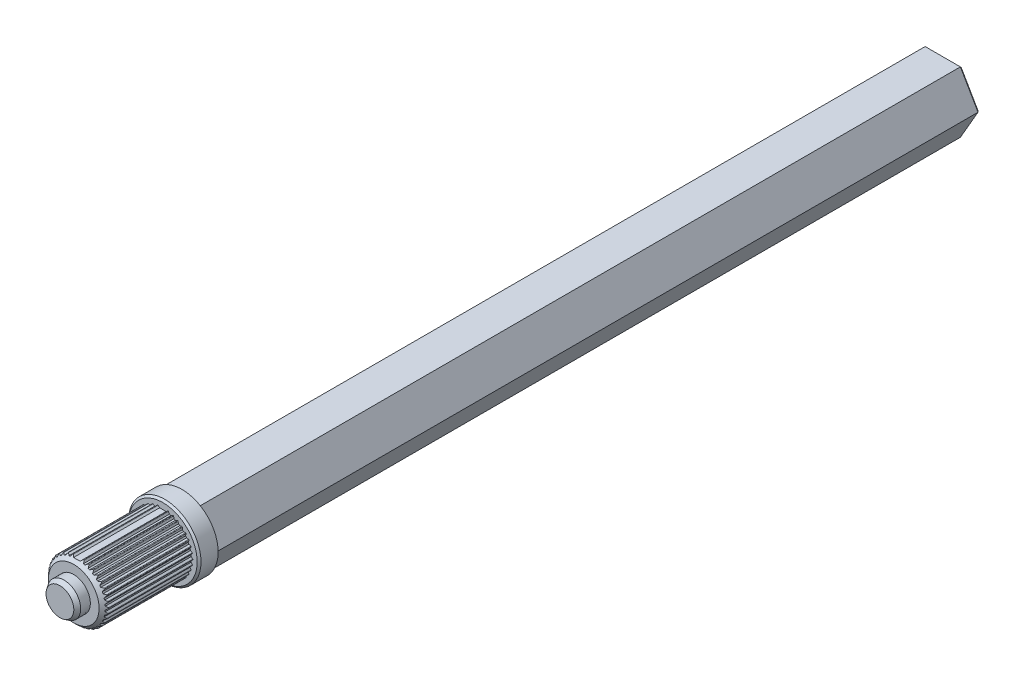
SolidWorks part; units mm, degrees
material "201 Tavlı Paslanmaz Çelik (SS)"
ref_plane "Ön Düzlem" through (0, 0, 0) normal (0, 0, 1) x (1, 0, 0)
ref_plane "Üst Düzlem" through (0, 0, 0) normal (0, 1, 0) x (1, 0, 0)
ref_plane "Sağ Düzlem" through (0, 0, 0) normal (1, 0, 0) x (0, 0, -1)
sketch "Çizim1" plane through (0, 0, 0) normal (0, 0, 1) x (1, 0, 0)
  line L1 (9.2376, 0) -> (4.6188, 8)
  line L2 (4.6188, 8) -> (-4.6188, 8)
  line L3 (-4.6188, 8) -> (-9.2376, 0)
  line L4 (-9.2376, 0) -> (-4.6188, -8)
  line L5 (-4.6188, -8) -> (4.6188, -8)
  line L6 (4.6188, -8) -> (9.2376, 0)
  circle A0 centre (0, 0) radius 8 construction
  dimension "D1" = 16
extrude "Yükseklik-Ekstrüzyon1" add sketch "Çizim1" along normal blind 200
sketch "Çizim2" plane through (0, 0, 200) normal (0, 0, 1) x (1, 0, 0)
  circle A0 centre (0, 0) radius 9.5
extrude "Yükseklik-Ekstrüzyon2" add sketch "Çizim2" along normal blind 5
sketch "Çizim3" plane through (0, 0, 205) normal (0, 0, 1) x (1, 0, 0)
  line L0 (5.9329, 5.1084) -> (5.4037, 5.1084)
  line L1 (5.1084, 5.9329) -> (5.1084, 5.4037)
  line L2 (6.7298, 4.0006) -> (6.2087, 4.0925)
  line L3 (6.061, 4.9557) -> (5.9692, 4.4346)
  line L4 (7.6922, 1.4576) -> (7.234, 1.7221)
  line L5 (7.3904, 2.5838) -> (7.1259, 2.1256)
  line L6 (7.3222, 2.7712) -> (6.825, 2.9521)
  line L7 (6.8295, 3.8279) -> (6.6485, 3.3307)
  line L8 (7.8285, 0.0997) -> (7.4231, 0.4398)
  line L9 (7.7268, -1.2612) -> (7.3867, -0.8559)
  line L10 (7.8285, -0.0997) -> (7.4231, -0.4398)
  line L11 (6.8295, -3.8279) -> (6.6485, -3.3307)
  line L12 (6.7298, -4.0006) -> (6.2087, -4.0925)
  line L13 (7.3222, -2.7712) -> (6.825, -2.9521)
  line L14 (7.3904, -2.5838) -> (7.1259, -2.1256)
  line L15 (7.6922, -1.4576) -> (7.234, -1.7221)
  line L16 (6.061, -4.9557) -> (5.9692, -4.4346)
  line L17 (5.9329, -5.1084) -> (5.4037, -5.1084)
  line L18 (5.1084, -5.9329) -> (5.1084, -5.4037)
  line L19 (7.7268, 1.2612) -> (7.3867, 0.8559)
  line L20 (3.8279, 6.8295) -> (3.3307, 6.6485)
  line L21 (2.5838, 7.3904) -> (2.1256, 7.1259)
  line L22 (1.2612, 7.7268) -> (0.8559, 7.3867)
  line L23 (1.4576, 7.6922) -> (1.7221, 7.234)
  line L24 (2.7712, 7.3222) -> (2.9521, 6.825)
  line L25 (-1.2612, 7.7268) -> (-0.8559, 7.3867)
  line L26 (-2.5838, 7.3904) -> (-2.1256, 7.1259)
  line L27 (-2.7712, 7.3222) -> (-2.9521, 6.825)
  line L28 (-1.4576, 7.6922) -> (-1.7221, 7.234)
  line L29 (-0.8559, 7.3867) -> (0.8559, 7.3867)
  line L30 (4.9557, 6.061) -> (4.4346, 5.9692)
  line L31 (4.0006, 6.7298) -> (4.0925, 6.2087)
  line L32 (-5.9329, 5.1084) -> (-5.4037, 5.1084)
  line L33 (-5.1084, 5.9329) -> (-5.1084, 5.4037)
  line L34 (-4.9557, 6.061) -> (-4.4346, 5.9692)
  line L35 (-6.7298, 4.0006) -> (-6.2087, 4.0925)
  line L36 (-6.061, 4.9557) -> (-5.9692, 4.4346)
  line L37 (-7.3222, 2.7712) -> (-6.825, 2.9521)
  line L38 (-7.6922, 1.4576) -> (-7.234, 1.7221)
  line L39 (-7.3904, 2.5838) -> (-7.1259, 2.1256)
  line L40 (-6.8295, 3.8279) -> (-6.6485, 3.3307)
  line L41 (-4.0006, 6.7298) -> (-4.0925, 6.2087)
  line L42 (-3.8279, 6.8295) -> (-3.3307, 6.6485)
  line L43 (4.9557, -6.061) -> (4.4346, -5.9692)
  line L44 (2.5838, -7.3904) -> (2.1256, -7.1259)
  line L45 (1.2612, -7.7268) -> (0.8559, -7.3867)
  line L46 (1.4576, -7.6922) -> (1.7221, -7.234)
  line L47 (2.7712, -7.3222) -> (2.9521, -6.825)
  line L48 (4.0006, -6.7298) -> (4.0925, -6.2087)
  line L49 (3.8279, -6.8295) -> (3.3307, -6.6485)
  line L50 (0.0997, -7.8285) -> (0.4398, -7.4231)
  line L51 (-0.0997, -7.8285) -> (-0.4398, -7.4231)
  line L52 (-1.2612, -7.7268) -> (-0.8559, -7.3867)
  line L53 (-2.5838, -7.3904) -> (-2.1256, -7.1259)
  line L54 (-2.7712, -7.3222) -> (-2.9521, -6.825)
  line L55 (-1.4576, -7.6922) -> (-1.7221, -7.234)
  line L56 (-7.8285, 0.0997) -> (-7.4231, 0.4398)
  line L57 (-7.7268, -1.2612) -> (-7.3867, -0.8559)
  line L58 (-7.8285, -0.0997) -> (-7.4231, -0.4398)
  line L59 (-7.3904, -2.5838) -> (-7.1259, -2.1256)
  line L60 (-6.8295, -3.8279) -> (-6.6485, -3.3307)
  line L61 (-6.7298, -4.0006) -> (-6.2087, -4.0925)
  line L62 (-7.3222, -2.7712) -> (-6.825, -2.9521)
  line L63 (-7.6922, -1.4576) -> (-7.234, -1.7221)
  line L64 (-5.9329, -5.1084) -> (-5.4037, -5.1084)
  line L65 (-4.9557, -6.061) -> (-4.4346, -5.9692)
  line L66 (-5.1084, -5.9329) -> (-5.1084, -5.4037)
  line L67 (-6.061, -4.9557) -> (-5.9692, -4.4346)
  line L68 (-4.0006, -6.7298) -> (-4.0925, -6.2087)
  line L69 (-3.8279, -6.8295) -> (-3.3307, -6.6485)
  line L70 (4.0811, -6.273) -> (-4.0811, -6.273) construction
  line L71 (-7.7268, 1.2612) -> (-7.3867, 0.8559)
  arc A0 (5.4037, 5.1084) -> (5.1084, 5.4037) centre (0, 0) ccw
  arc A1 (6.8295, 3.8279) -> (6.7298, 4.0006) centre (6.7072, 3.8724) ccw
  arc A2 (6.2087, 4.0925) -> (5.9692, 4.4346) centre (0, 0) ccw
  arc A3 (6.061, 4.9557) -> (5.9329, 5.1084) centre (5.9329, 4.9783) ccw
  arc A4 (7.3904, 2.5838) -> (7.3222, 2.7712) centre (7.2777, 2.6489) ccw
  arc A5 (7.7268, 1.2612) -> (7.6922, 1.4576) centre (7.6271, 1.3449) ccw
  arc A6 (6.825, 2.9521) -> (6.6485, 3.3307) centre (0, 0) ccw
  arc A7 (7.234, 1.7221) -> (7.1259, 2.1256) centre (0, 0) ccw
  arc A8 (7.8285, -0.0997) -> (7.8285, 0.0997) centre (7.7448, 0) ccw
  arc A9 (7.4231, 0.4398) -> (7.3867, 0.8559) centre (0, 0) ccw
  arc A10 (7.3867, -0.8559) -> (7.4231, -0.4398) centre (0, 0) ccw
  arc A11 (7.6922, -1.4576) -> (7.7268, -1.2612) centre (7.6271, -1.3449) ccw
  arc A12 (7.3222, -2.7712) -> (7.3904, -2.5838) centre (7.2777, -2.6489) ccw
  arc A13 (7.1259, -2.1256) -> (7.234, -1.7221) centre (0, 0) ccw
  arc A14 (6.7298, -4.0006) -> (6.8295, -3.8279) centre (6.7072, -3.8724) ccw
  arc A15 (6.6485, -3.3307) -> (6.825, -2.9521) centre (0, 0) ccw
  arc A16 (5.1084, -5.4037) -> (5.4037, -5.1084) centre (0, 0) ccw
  arc A17 (5.9329, -5.1084) -> (6.061, -4.9557) centre (5.9329, -4.9783) ccw
  arc A18 (5.9692, -4.4346) -> (6.2087, -4.0925) centre (0, 0) ccw
  arc A19 (3.3307, 6.6485) -> (2.9521, 6.825) centre (0, 0) ccw
  arc A20 (4.0006, 6.7298) -> (3.8279, 6.8295) centre (3.8724, 6.7072) ccw
  arc A21 (1.4576, 7.6922) -> (1.2612, 7.7268) centre (1.3449, 7.6271) ccw
  arc A22 (2.7712, 7.3222) -> (2.5838, 7.3904) centre (2.6489, 7.2777) ccw
  arc A23 (2.1256, 7.1259) -> (1.7221, 7.234) centre (0, 0) ccw
  arc A24 (-1.2612, 7.7268) -> (-1.4576, 7.6922) centre (-1.3449, 7.6271) ccw
  arc A25 (-1.7221, 7.234) -> (-2.1256, 7.1259) centre (0, 0) ccw
  arc A26 (-2.9521, 6.825) -> (-3.3307, 6.6485) centre (0, 0) ccw
  arc A27 (-2.5838, 7.3904) -> (-2.7712, 7.3222) centre (-2.6489, 7.2777) ccw
  arc A28 (4.4346, 5.9692) -> (4.0925, 6.2087) centre (0, 0) ccw
  arc A29 (-3.8279, 6.8295) -> (-4.0006, 6.7298) centre (-3.8724, 6.7072) ccw
  arc A30 (-4.0925, 6.2087) -> (-4.4346, 5.9692) centre (0, 0) ccw
  arc A31 (-5.1084, 5.4037) -> (-5.4037, 5.1084) centre (0, 0) ccw
  arc A32 (-4.9557, 6.061) -> (-5.1084, 5.9329) centre (-4.9783, 5.9329) ccw
  arc A33 (-6.7298, 4.0006) -> (-6.8295, 3.8279) centre (-6.7072, 3.8724) ccw
  arc A34 (-5.9329, 5.1084) -> (-6.061, 4.9557) centre (-5.9329, 4.9783) ccw
  arc A35 (-5.9692, 4.4346) -> (-6.2087, 4.0925) centre (0, 0) ccw
  arc A36 (-6.6485, 3.3307) -> (-6.825, 2.9521) centre (0, 0) ccw
  arc A37 (-7.3222, 2.7712) -> (-7.3904, 2.5838) centre (-7.2777, 2.6489) ccw
  arc A38 (-7.1259, 2.1256) -> (-7.234, 1.7221) centre (0, 0) ccw
  arc A39 (-7.6922, 1.4576) -> (-7.7268, 1.2612) centre (-7.6271, 1.3449) ccw
  arc A41 (4.0925, -6.2087) -> (4.4346, -5.9692) centre (0, 0) ccw
  arc A42 (3.8279, -6.8295) -> (4.0006, -6.7298) centre (3.8724, -6.7072) ccw
  arc A43 (2.5838, -7.3904) -> (2.7712, -7.3222) centre (2.6489, -7.2777) ccw
  arc A44 (1.2612, -7.7268) -> (1.4576, -7.6922) centre (1.3449, -7.6271) ccw
  arc A45 (1.7221, -7.234) -> (2.1256, -7.1259) centre (0, 0) ccw
  arc A46 (2.9521, -6.825) -> (3.3307, -6.6485) centre (0, 0) ccw
  arc A47 (-0.0997, -7.8285) -> (0.0997, -7.8285) centre (0, -7.7448) ccw
  arc A48 (-1.4576, -7.6922) -> (-1.2612, -7.7268) centre (-1.3449, -7.6271) ccw
  arc A49 (-0.8559, -7.3867) -> (-0.4398, -7.4231) centre (0, 0) ccw
  arc A50 (-2.1256, -7.1259) -> (-1.7221, -7.234) centre (0, 0) ccw
  arc A51 (-2.7712, -7.3222) -> (-2.5838, -7.3904) centre (-2.6489, -7.2777) ccw
  arc A52 (-3.3307, -6.6485) -> (-2.9521, -6.825) centre (0, 0) ccw
  arc A53 (0.4398, -7.4231) -> (0.8559, -7.3867) centre (0, 0) ccw
  arc A54 (-7.8285, 0.0997) -> (-7.8285, -0.0997) centre (-7.7448, 0) ccw
  arc A55 (-7.3867, 0.8559) -> (-7.4231, 0.4398) centre (0, 0) ccw
  arc A56 (-7.4231, -0.4398) -> (-7.3867, -0.8559) centre (0, 0) ccw
  arc A57 (-7.7268, -1.2612) -> (-7.6922, -1.4576) centre (-7.6271, -1.3449) ccw
  arc A58 (-7.3904, -2.5838) -> (-7.3222, -2.7712) centre (-7.2777, -2.6489) ccw
  arc A59 (-7.234, -1.7221) -> (-7.1259, -2.1256) centre (0, 0) ccw
  arc A60 (-6.825, -2.9521) -> (-6.6485, -3.3307) centre (0, 0) ccw
  arc A61 (-6.8295, -3.8279) -> (-6.7298, -4.0006) centre (-6.7072, -3.8724) ccw
  arc A62 (-5.4037, -5.1084) -> (-5.1084, -5.4037) centre (0, 0) ccw
  arc A63 (-4.4346, -5.9692) -> (-4.0925, -6.2087) centre (0, 0) ccw
  arc A64 (-5.1084, -5.9329) -> (-4.9557, -6.061) centre (-4.9783, -5.9329) ccw
  arc A65 (-6.061, -4.9557) -> (-5.9329, -5.1084) centre (-5.9329, -4.9783) ccw
  arc A66 (-4.0006, -6.7298) -> (-3.8279, -6.8295) centre (-3.8724, -6.7072) ccw
  arc A67 (-6.2087, -4.0925) -> (-5.9692, -4.4346) centre (0, 0) ccw
  arc A68 (4.9557, -6.061) -> (5.1084, -5.9329) centre (4.9783, -5.9329) ccw
  arc A69 (5.1084, 5.9329) -> (4.9557, 6.061) centre (4.9783, 5.9329) ccw
extrude "Yükseklik-Ekstrüzyon3" add sketch "Çizim3" along normal blind 27
sketch "Çizim6" plane through (0, 0, 0) normal (0, 1, 0) x (1, 0, 0)
  line L1 (7.9127, -227.0216) -> (6.6518, -228.372)
  line L2 (0.8559, -232) -> (-0.8559, -232) construction
  line L3 (7.9127, -227.0216) -> (8.2802, -227.1262)
  line L4 (0, -232) -> (0, -234.5555)
  line L5 (3.6441, -231.9996) -> (0, -232)
  line L6 (0, -234.5555) -> (11.626, -234.5555)
  line L7 (11.626, -234.5555) -> (11.626, -227.1262)
  line L8 (11.626, -227.1262) -> (8.2802, -227.1262)
  line L13 (6.6518, -228.372) -> (4.3531, -228.3722)
  line L14 (4.3531, -228.3722) -> (4.3534, -230.8996)
  line L15 (4.3534, -230.8996) -> (3.6441, -231.9996)
  dimension "D6" = 2.2986
  dimension "D7" = 2.5274
  dimension "D8" = 1.3089
revolve "Kes-Döndür2" cut sketch "Çizim6" angle 360 about L4
chamfer "Pah1" distance 0.5 angle 45 7 edges at (-6.9282, 4, 0) (-6.9282, -4, 0) (0, -8, 0) (6.9282, -4, 0) (0, 8, 0) (6.9282, 4, 0) (9.5, 0, 205)
